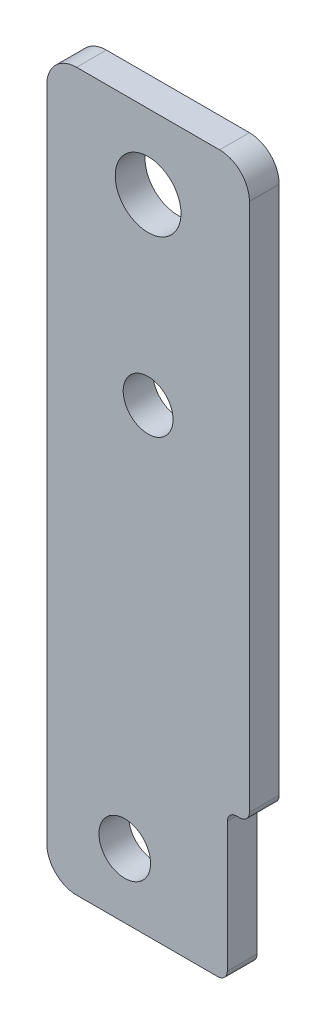
SolidWorks part; units mm, degrees
material "3003 Alloy"
ref_plane "X-Y Datum" through (0, 0, 0) normal (0, 0, 1) x (1, 0, 0)
ref_plane "X-Z Datum" through (0, 0, 0) normal (0, 1, 0) x (1, 0, 0)
ref_plane "Y-Z Datum" through (0, 0, 0) normal (1, 0, 0) x (0, 0, -1)
sketch "Sketch1" plane through (0, 0, 0) normal (0, 0, 1) x (1, 0, 0)
  line L1 (-10.795, 31.115) -> (10.795, 31.115)
  line L2 (-10.795, 31.115) -> (-10.795, -31.115)
  line L4 (10.795, 31.115) -> (10.795, -31.115)
  line L5 (-10.795, 31.115) -> (10.795, -31.115) construction
  line L6 (-10.795, -31.115) -> (10.795, 31.115) construction
  line L8 (-10.795, -31.115) -> (-10.795, -45.2786)
  line L9 (-10.795, -45.2786) -> (10.795, -45.2786)
  line L10 (10.795, -45.2786) -> (10.795, -31.115)
  circle A0 centre (0, 23.1775) radius 3.5052
  circle A2 centre (0, 23.1775) radius 3.5052 construction
  circle A3 centre (0, 3.7344) radius 2.4 construction
  circle A4 centre (0, 3.7344) radius 2.4 construction
  circle A5 centre (-2.4892, -38.4124) radius 2.7508
  circle A6 centre (0, 3.7344) radius 2.654
  point P0 (0, 0)
  dimension "D3" = 0.254
  dimension "D1" = 62.23
  dimension "D2" = 21.59
  dimension "D5" = 7.9375
extrude "Boss-Extrude1" add sketch "Sketch1" along normal blind 3.175
fillet "Fillet1" radius 3.175 4 edges at (-10.795, 31.115, 1.5875) (10.795, 31.115, 1.5875) (10.795, -45.2786, 1.5875) (-10.795, -45.2786, 1.5875)
sketch "Sketch3" plane through (0, 0, 3.175) normal (0, 0, 1) x (1, 0, 0)
  line L1 (10.976, -45.3138) -> (8.436, -45.3138)
  line L2 (10.976, -45.3138) -> (10.976, -29.4458)
  line L3 (10.976, -29.4458) -> (8.436, -29.4458)
  line L4 (8.436, -45.3138) -> (8.436, -29.4458)
extrude "Cut-Extrude2" cut sketch "Sketch3" against normal through all
fillet "Fillet2" radius 1 3 edges at (10.795, -29.4458, 1.5875) (8.436, -29.4458, 1.5875) (8.436, -45.172, 1.5875)
